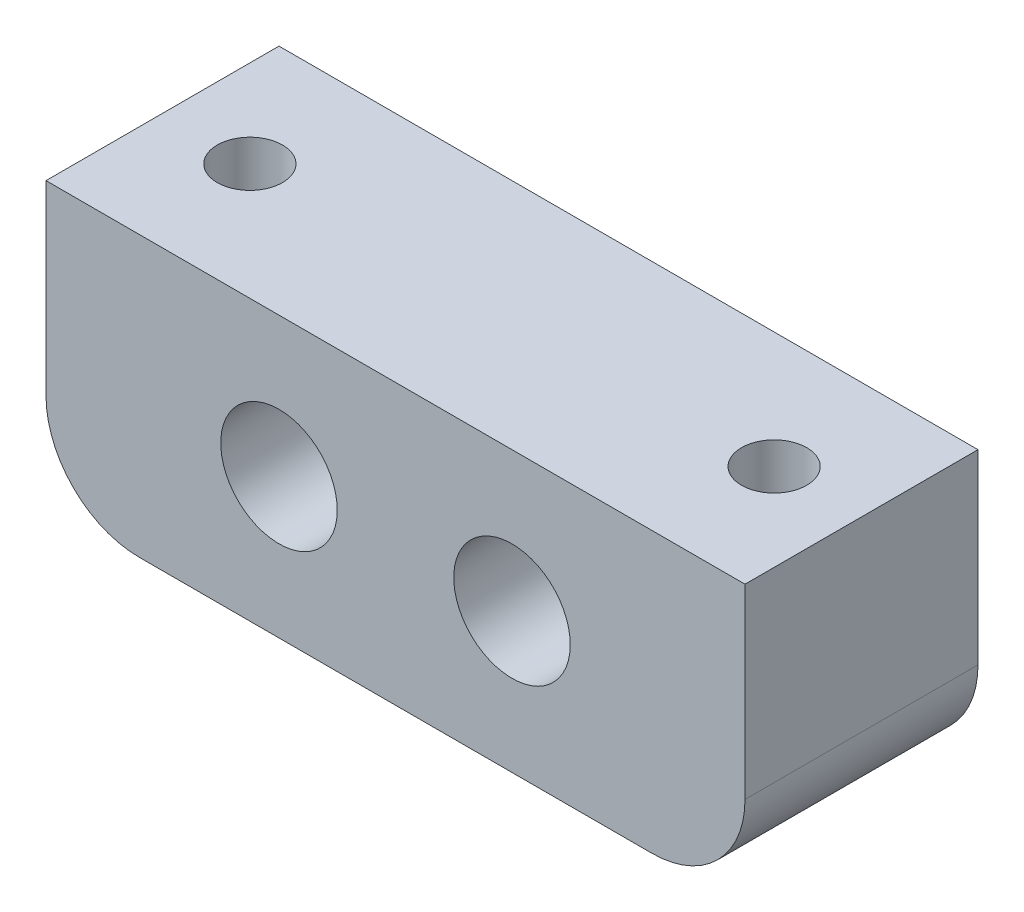
SolidWorks part; units mm, degrees
ref_plane "Front Plane" through (0, 0, 0) normal (0, 0, 1) x (1, 0, 0)
ref_plane "Top Plane" through (0, 0, 0) normal (0, 1, 0) x (1, 0, 0)
ref_plane "Right Plane" through (0, 0, 0) normal (1, 0, 0) x (0, 0, -1)
sketch "Sketch1" plane through (0, 0, 0) normal (0, 0, 1) x (1, 0, 0)
  line L1 (-6.1932, -0.0935) -> (12.8568, -0.0935)
  line L2 (-6.1932, -0.0935) -> (-6.1932, -5.1735)
  line L3 (-3.6532, -7.7135) -> (10.3168, -7.7135)
  line L4 (12.8568, -0.0935) -> (12.8568, -5.1735)
  circle A0 centre (0.1568, -3.9035) radius 1.5875
  circle A1 centre (6.5068, -3.9035) radius 1.5875
  arc A2 (10.3168, -7.7135) -> (12.8568, -5.1735) centre (10.3168, -5.1735) ccw
  arc A3 (-6.1932, -5.1735) -> (-3.6532, -7.7135) centre (-3.6532, -5.1735) ccw
  point P10 (12.8568, -7.7135)
  point P13 (-6.1932, -7.7135)
  dimension "D3" = 3.175
  dimension "D4" = 3.175
  dimension "D5" = 2.54
  dimension "D6" = 6.35
  dimension "D7" = 6.35
  dimension "D8" = 3.81
  dimension "D9" = 3.81
  dimension "D1" = 19.05
  dimension "D2" = 7.62
extrude "Boss-Extrude1" add sketch "Sketch1" along normal blind 6.35
sketch "Sketch2" plane through (0, -0.0935, 0) normal (0, 1, 0) x (1, 0, 0)
  line L0 (12.8568, -6.35) -> (12.8568, 0) construction
  line L1 (-6.1932, -6.35) -> (-6.1932, 0) construction
  circle A0 centre (-3.812, -3.175) radius 0.889
  circle A1 centre (10.4755, -3.175) radius 0.889
  dimension "D1" = 1.778
  dimension "D2" = 1.778
  dimension "D3" = 2.3813
  dimension "D4" = 2.3813
  dimension "D5" = 14.2875
extrude "Cut-Extrude1" cut sketch "Sketch2" against normal blind 6.35
